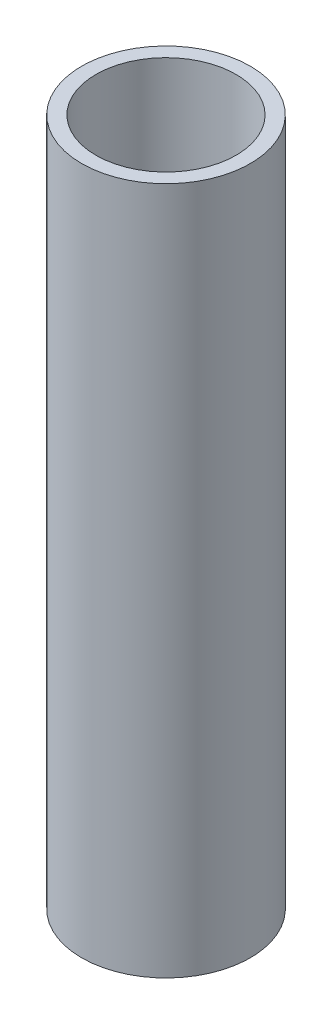
SolidWorks part; units mm, degrees
ref_plane "Front" through (0, 0, 0) normal (0, 0, 1) x (1, 0, 0)
ref_plane "Top" through (0, 0, 0) normal (0, 1, 0) x (1, 0, 0)
ref_plane "Right" through (0, 0, 0) normal (1, 0, 0) x (0, 0, -1)
sketch "Sketch1" plane through (0, 0, 0) normal (0, 1, 0) x (1, 0, 0)
  circle A0 centre (0, 0) radius 37.465
  circle A1 centre (0, 0) radius 41.275
  dimension "D1" = 74.93
  dimension "D2" = 82.55
extrude "Boss-Extrude1" add sketch "Sketch1" along normal blind 336.55 contours A1 A0
sketch "Sketch2" plane through (0, 336.55, 0) normal (0, 1, 0) x (1, 0, 0)
  circle A0 centre (0, 0) radius 34.29
  circle A1 centre (0, 0) radius 39.6617
  dimension "D1" = 68.58
extrude "Boss-Extrude2" add sketch "Sketch2" against normal blind 93.472
